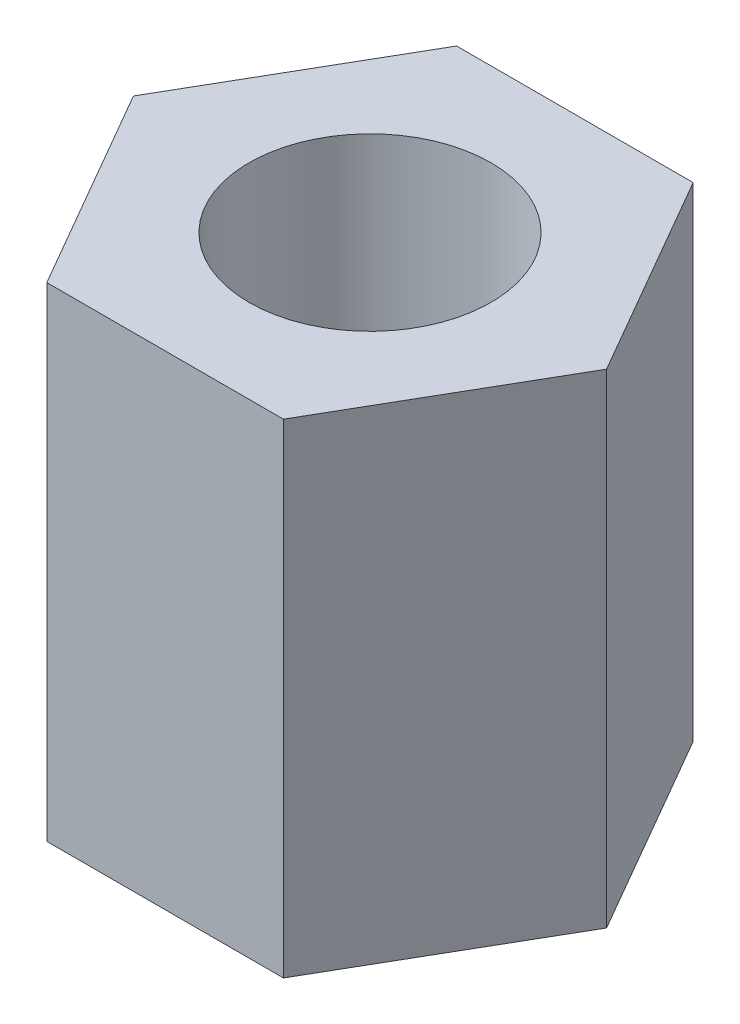
SolidWorks part; units mm, degrees
material "Nylon 101"
ref_plane "Front Plane" through (0, 0, 0) normal (0, 0, 1) x (1, 0, 0)
ref_plane "Top Plane" through (0, 0, 0) normal (0, 1, 0) x (1, 0, 0)
ref_plane "Right Plane" through (0, 0, 0) normal (1, 0, 0) x (0, 0, -1)
sketch "Sketch1" plane through (0, 0, 0) normal (0, 1, 0) x (1, 0, 0)
  line L0 (0, 0) -> (50000, 0) construction
  line L1 (0, 0) -> (0, 50000) construction
  line L2 (1.4665, 2.54) -> (-1.4665, 2.54)
  line L3 (-1.4665, 2.54) -> (-2.9329, 0)
  line L4 (1.4665, 2.54) -> (2.9329, 0)
  line L5 (1.4665, -2.54) -> (2.9329, 0)
  line L6 (-1.4665, -2.54) -> (-2.9329, 0)
  line L7 (1.4665, -2.54) -> (-1.4665, -2.54)
  circle A0 centre (0, 0) radius 1.5
  point P11 (0, 2.54)
  point P14 (0, -2.54)
  point P15 (-1.7951, 3.1605)
  point P16 (1.9986, 3.9568)
  dimension "D1" = 3
  dimension "D2" = 5.08
  dimension "D3" = 5.08
extrude "Boss-Extrude1" add sketch "Sketch1" along normal blind 6
equation "\"D3@Sketch1\"=\"D2@Sketch1\""
